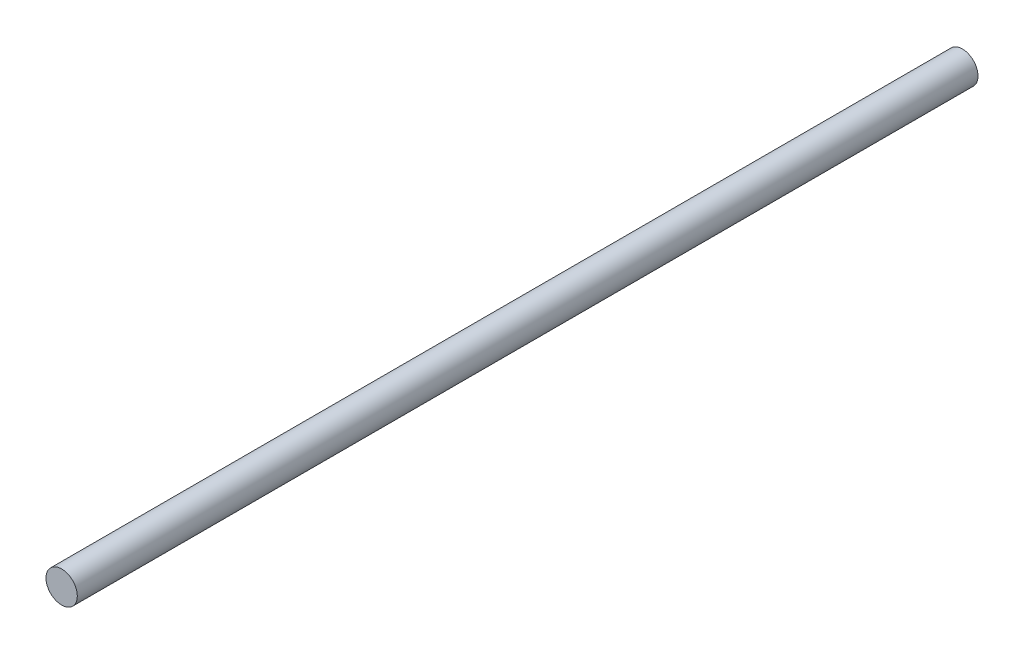
SolidWorks part; units mm, degrees
ref_plane "Front Plane" through (0, 0, 0) normal (0, 0, 1) x (1, 0, 0)
ref_plane "Top Plane" through (0, 0, 0) normal (0, 1, 0) x (1, 0, 0)
ref_plane "Right Plane" through (0, 0, 0) normal (1, 0, 0) x (0, 0, -1)
sketch "Sketch2" plane through (0, 0, 18) normal (0, 0, -1) x (-1, 0, 0)
  circle A0 centre (0, 0) radius 4
  dimension "D1" = 8
extrude "Boss-Extrude1" add sketch "Sketch2" against normal blind 300
sketch "Sketch3" plane through (0, 0, 318) normal (0, 0, 1) x (1, 0, 0)
  circle A1 centre (0, 0) radius 4
  circle A2 centre (0, 0) radius 4
  dimension "D1" = 0
extrude "Cut-Extrude1" cut sketch "Sketch3" against normal blind 70
